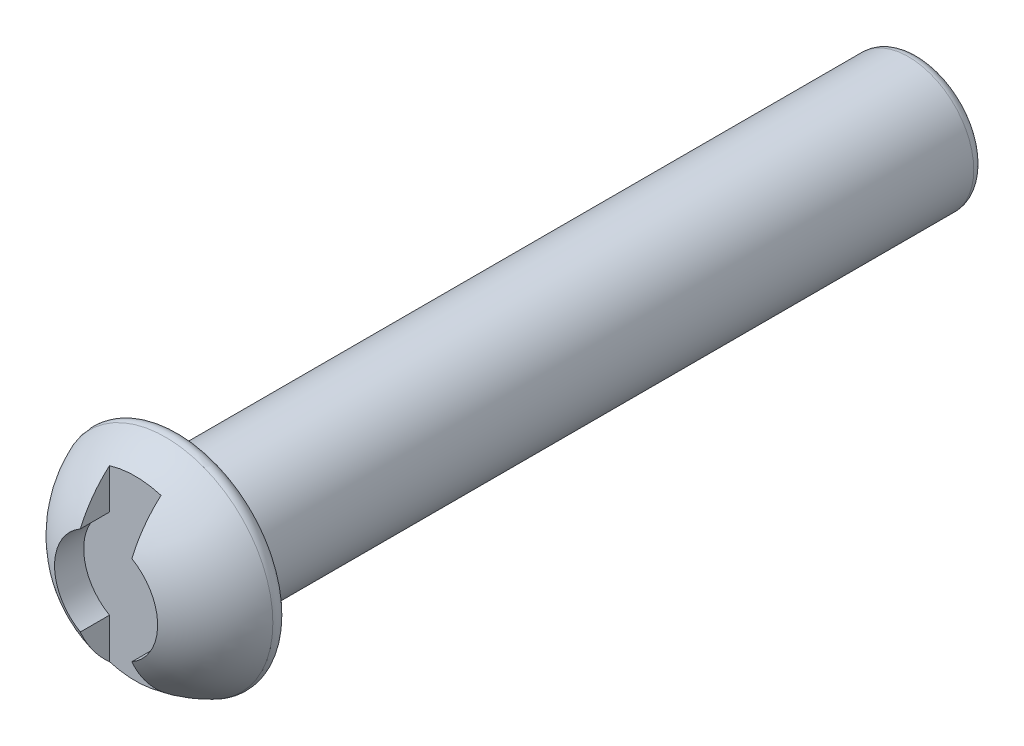
SolidWorks part; units mm, degrees
ref_plane "Front Plane" through (0, 0, 0) normal (0, 0, 1) x (1, 0, 0)
ref_plane "Top Plane" through (0, 0, 0) normal (0, 1, 0) x (1, 0, 0)
ref_plane "Right Plane" through (0, 0, 0) normal (1, 0, 0) x (0, 0, -1)
sketch "Sketch4" plane through (0, 0, 0) normal (1, 0, 0) x (0, 0, -1)
  line L0 (0, 0) -> (12, 0)
  line L1 (12, 0) -> (12, 0.95)
  line L2 (12, 0.95) -> (1.25, 0.95)
  line L3 (1.25, 1.63) -> (1.25, 0.95)
  arc A0 (1.25, 1.63) -> (0, 0) centre (1.6878, 0) ccw
  point P7 (0, 0)
  dimension "D1" = 12
  dimension "D2" = 0.95
  dimension "D3" = 1.63
  dimension "D4" = 1.25
revolve "Revolve2" add sketch "Sketch4" angle 360 about L0
sketch "Sketch5" plane through (0, 0, 0) normal (0, 0, 1) x (1, 0, 0)
  line L0 (-0.375, -0.6495) -> (-0.375, -1.871)
  line L1 (0.375, 1.871) -> (-0.375, 1.871)
  line L2 (0.375, 1.871) -> (0.375, 0.6495)
  line L3 (0.375, -1.871) -> (-0.375, -1.871)
  line L4 (-0.375, 1.871) -> (-0.375, 0.6495)
  line L9 (0.375, -0.6495) -> (0.375, -1.871)
  arc A0 (-0.375, 0.6495) -> (-0.375, -0.6495) centre (0, 0) ccw
  arc A1 (0.375, -0.6495) -> (0.375, 0.6495) centre (0, 0) ccw
  point P0 (0, 0)
  dimension "D2" = 1.5
  dimension "D1" = 0.75
extrude "Cut-Extrude1" cut sketch "Sketch5" against normal blind 0.6
fillet "Fillet1" radius 0.15 2 edges at (1.63, 0, -1.25) (0.95, 0, -12)
